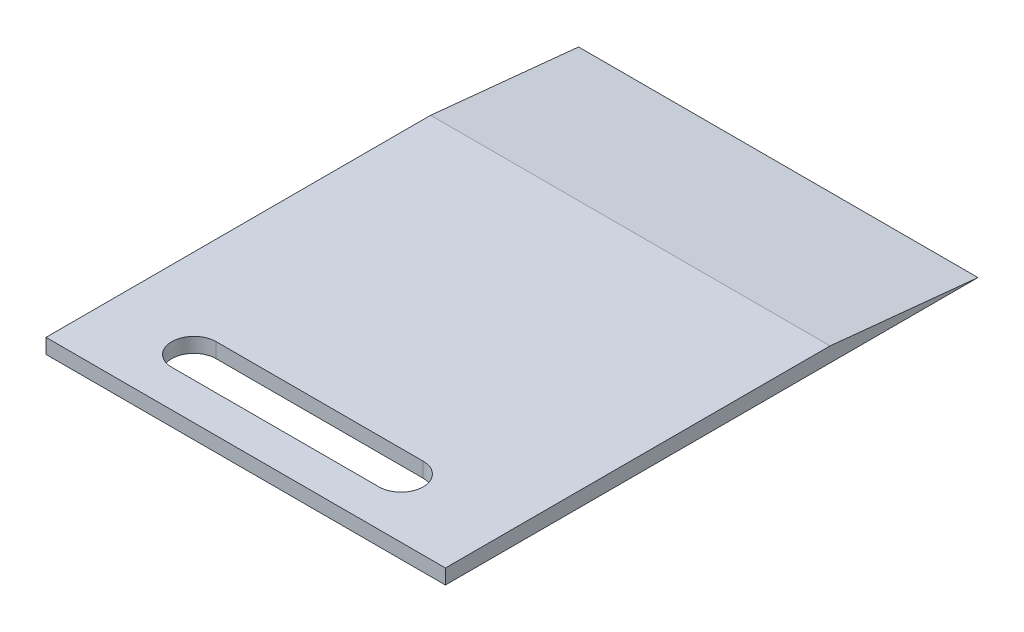
SolidWorks part; units mm, degrees
material "1023 Chapa de acero al carbono (SS)"
ref_plane "Alzado" through (0, 0, 0) normal (0, 0, 1) x (1, 0, 0)
ref_plane "Planta" through (0, 0, 0) normal (0, 1, 0) x (1, 0, 0)
ref_plane "Vista lateral" through (0, 0, 0) normal (1, 0, 0) x (0, 0, -1)
sketch "Croquis1" plane through (0, 0, 0) normal (1, 0, 0) x (0, 0, -1)
  line L0 (0, 0) -> (18, 0)
  line L1 (18, 0) -> (13, 0.5)
  line L2 (13, 0.5) -> (0, 0.5)
  line L3 (0, 0.5) -> (0, 0)
  dimension "D1" = 0.5
  dimension "D2" = 18
  dimension "D3" = 5
extrude "Saliente-Extruir1" add sketch "Croquis1" along normal blind 13.5
sketch "Croquis2" plane through (0, 0.5, 0) normal (0, 1, 0) x (1, 0, 0)
  line L0 (3, 2) -> (10, 2) construction
  line L1 (3, 2.75) -> (10, 2.75)
  line L2 (3, 1.25) -> (10, 1.25)
  line L4 (13.5, 18) -> (0, 18) construction
  line L8 (0, 13) -> (0, 0)
  line L9 (0, 0) -> (13.5, 0)
  line L10 (13.5, 0) -> (13.5, 13)
  line L11 (13.5, 13) -> (0, 13)
  line L12 (0, 13) -> (0, 0)
  line L13 (0, 0) -> (13.5, 0)
  line L14 (13.5, 0) -> (13.5, 13)
  line L15 (13.5, 13) -> (0, 13)
  arc A0 (3, 2.75) -> (3, 1.25) centre (3, 2) ccw
  arc A1 (10, 1.25) -> (10, 2.75) centre (10, 2) ccw
  point P2 (6.5, 2)
  point P9 (6.75, 0)
  dimension "D1" = 16
  dimension "D2" = 1.5
  dimension "D4" = 7
  dimension "D5" = 3.75
  dimension "D3" = 0
extrude "Cortar-Extruir1" cut sketch "Croquis2" against normal through all contours L2 A1 L1 A0
